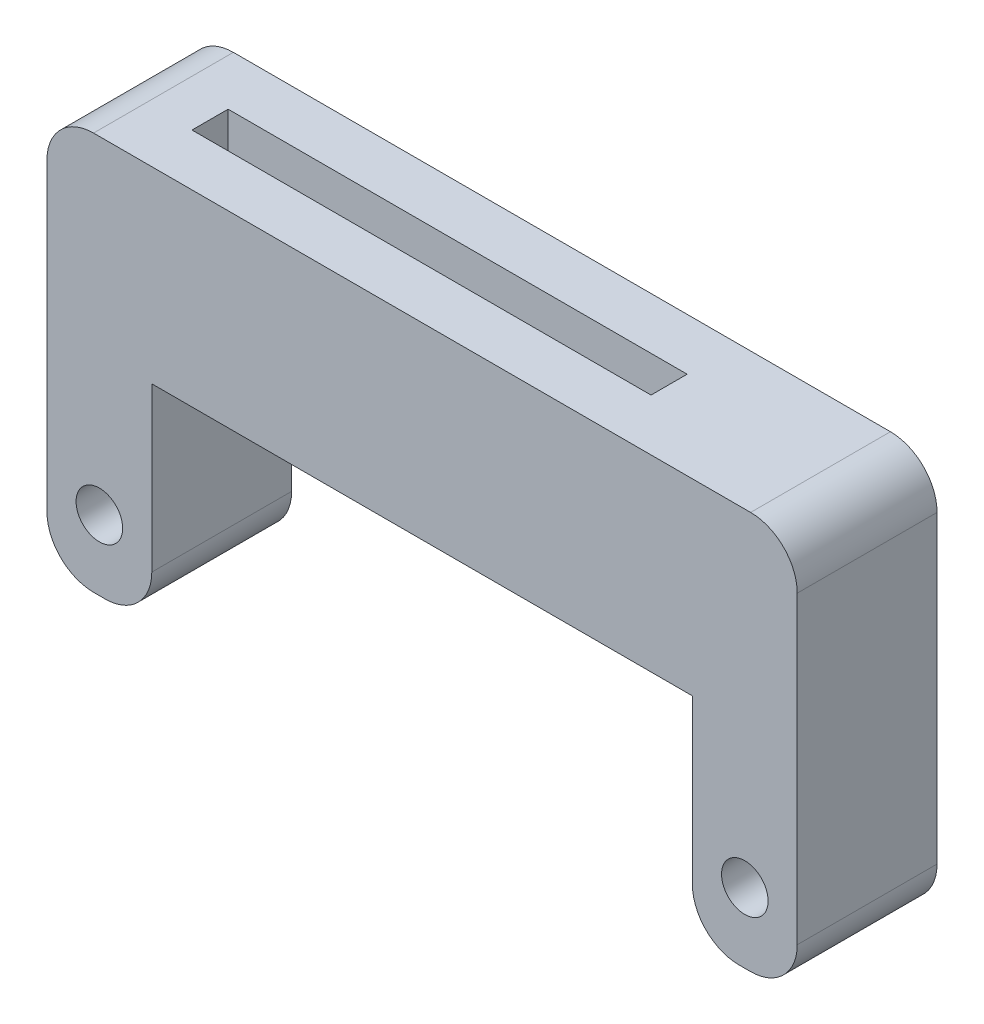
SolidWorks part; units mm, degrees
ref_plane "Front Plane" through (0, 0, 0) normal (0, 0, 1) x (1, 0, 0)
ref_plane "Top Plane" through (0, 0, 0) normal (0, 1, 0) x (1, 0, 0)
ref_plane "Right Plane" through (0, 0, 0) normal (1, 0, 0) x (0, 0, -1)
sketch "Sketch2" plane through (0, 0, 0) normal (0, 0, 1) x (1, 0, 0)
  line L1 (-16.1, -8.534) -> (16.1, -8.534)
  line L2 (-16.1, -8.534) -> (-16.1, 8.534)
  line L3 (-16.1, 8.534) -> (16.1, 8.534)
  line L4 (16.1, -8.534) -> (16.1, 8.534)
  line L5 (-16.1, -8.534) -> (16.1, 8.534) construction
  line L6 (-16.1, 8.534) -> (16.1, -8.534) construction
  point P0 (0, 0)
  dimension "D1" = 17.068
  dimension "D2" = 32.2
extrude "Boss-Extrude1" add sketch "Sketch2" along normal mid plane 6
sketch "Sketch3" plane through (0, 8.534, 0) normal (0, 1, 0) x (1, 0, 0)
  line L0 (-16.1, -3) -> (-16.1, 3) construction
  line L1 (-12.1, 0.775) -> (7.6, 0.775)
  line L2 (-12.1, 0.775) -> (-12.1, -0.775)
  line L3 (-12.1, -0.775) -> (7.6, -0.775)
  line L4 (7.6, 0.775) -> (7.6, -0.775)
  line L5 (16.1, -3) -> (16.1, 3) construction
  line L7 (-11.9825, 0) -> (7.6, 0) construction
  line L8 (-16.1, 0) -> (16.1, 0) construction
  dimension "D1" = 1.55
  dimension "D2" = 4
  dimension "D3" = 8.5
extrude "Cut-Extrude1" cut sketch "Sketch3" against normal blind 5
sketch "Sketch4" plane through (0, 0, 3) normal (0, 0, 1) x (1, 0, 0)
  line L0 (-16.1, -8.534) -> (16.1, -8.534) construction
  line L1 (-11.6, -8.534) -> (11.6, -8.534)
  line L2 (-11.6, -8.534) -> (-11.6, 0.466)
  line L3 (-11.6, 0.466) -> (11.6, 0.466)
  line L4 (11.6, -8.534) -> (11.6, 0.466)
  line L5 (-16.1, 8.534) -> (-16.1, -8.534) construction
  line L6 (16.1, -8.534) -> (16.1, 8.534) construction
  dimension "D1" = 9
  dimension "D2" = 4.5
  dimension "D3" = 4.5
extrude "Cut-Extrude2" cut sketch "Sketch4" against normal through all
sketch "Sketch5" plane through (0, 0, 3) normal (0, 0, 1) x (1, 0, 0)
  line L0 (-16.1, 8.534) -> (-16.1, -8.534) construction
  line L1 (16.1, -8.534) -> (16.1, 8.534) construction
  line L2 (-16.1, -8.534) -> (-11.6, -8.534) construction
  circle A0 centre (-13.85, -5.534) radius 1
  circle A2 centre (13.85, -5.534) radius 1
  dimension "D1" = 2
  dimension "D2" = 2.25
  dimension "D3" = 2.25
  dimension "D4" = 3
extrude "Cut-Extrude3" cut sketch "Sketch5" against normal through all
fillet "Fillet1" radius 2 6 edges at (-16.1, -8.534, 0) (-11.6, -8.534, 0) (11.6, -8.534, 0) (16.1, -8.534, 0) (16.1, 8.534, 0) (-16.1, 8.534, 0)
